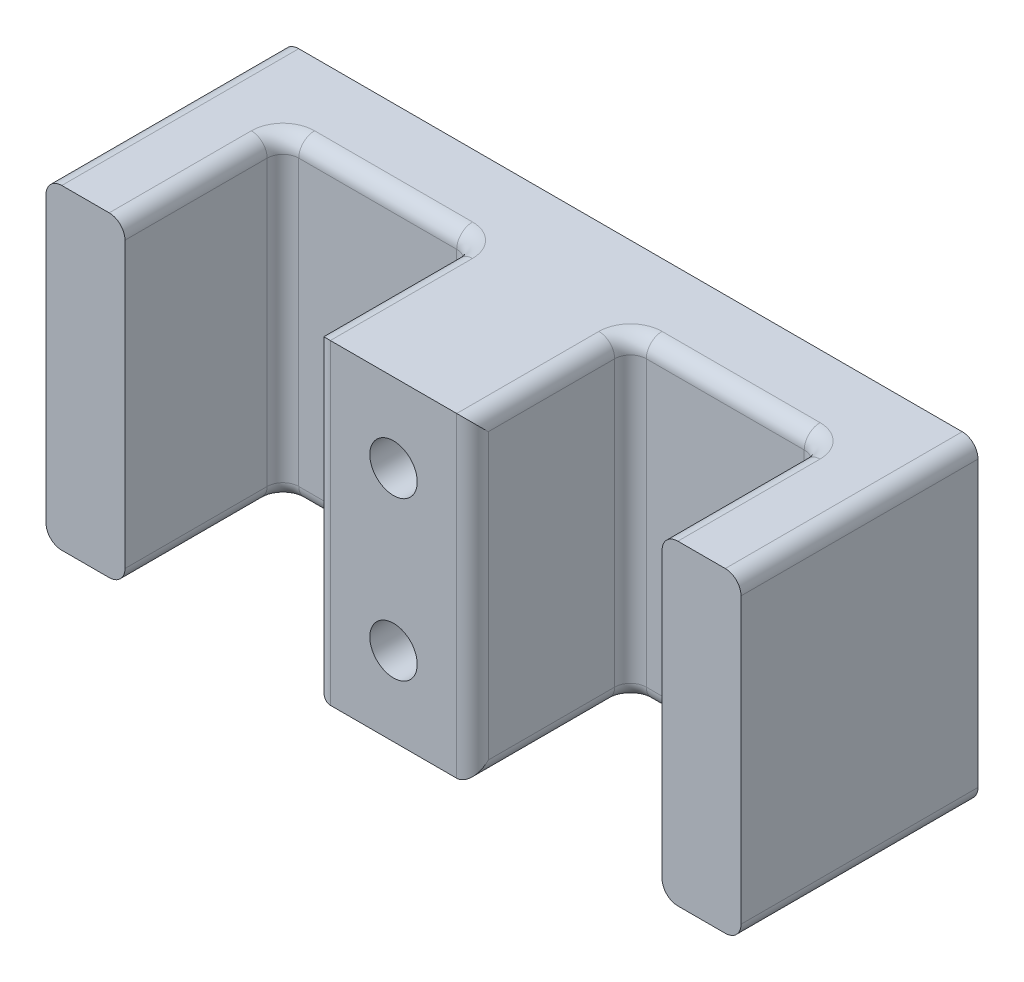
SolidWorks part; units mm, degrees
ref_plane "Front Plane" through (0, 0, 0) normal (0, 0, 1) x (1, 0, 0)
ref_plane "Top Plane" through (0, 0, 0) normal (0, 1, 0) x (1, 0, 0)
ref_plane "Right Plane" through (0, 0, 0) normal (1, 0, 0) x (0, 0, -1)
sketch "Sketch1" plane through (0, 0, 0) normal (0, 0, 1) x (1, 0, 0)
  line L0 (0, 0) -> (44, 0)
  line L1 (44, 0) -> (44, 20)
  line L2 (44, 20) -> (0, 20)
  line L3 (0, 20) -> (0, 0)
  dimension "D1" = 44
  dimension "D2" = 20
extrude "Boss-Extrude1" add sketch "Sketch1" along normal blind 5
sketch "Sketch2" plane through (0, 0, 5) normal (0, 0, 1) x (1, 0, 0)
  line L0 (0, 0) -> (5, 0)
  line L1 (0, 0) -> (44, 0) construction
  line L2 (5, 0) -> (5, 20)
  line L3 (44, 20) -> (0, 20) construction
  line L4 (5, 20) -> (0, 20)
  line L5 (0, 20) -> (0, 0)
  line L6 (17, 20) -> (27, 20)
  line L7 (27, 20) -> (27, 0)
  line L8 (27, 0) -> (17, 0)
  line L9 (17, 0) -> (17, 20)
  line L10 (44, 0) -> (44, 20)
  line L11 (44, 20) -> (39, 20)
  line L12 (39, 20) -> (39, 0)
  line L13 (39, 0) -> (44, 0)
  dimension "D1" = 5
  dimension "D2" = 5
  dimension "D3" = 10
  dimension "D4" = 12
extrude "Boss-Extrude2" add sketch "Sketch2" along normal blind 10
sketch "Sketch4" plane through (0, 0, 5) normal (0, 0, 1) x (1, 0, 0)
  line L0 (17, 20) -> (5, 20) construction
  line L1 (39, 20) -> (27, 20) construction
  line L2 (5, 0) -> (5, 20) construction
  line L3 (27, 0) -> (27, 20) construction
  circle A0 centre (11, 10) radius 1.75
  circle A1 centre (33, 10) radius 1.75
  dimension "D1" = 3.5
  dimension "D2" = 3.5
  dimension "D3" = 10
  dimension "D4" = 10
  dimension "D5" = 6
  dimension "D6" = 6
extrude "Cut-Extrude1" cut sketch "Sketch4" against normal up to next
sketch "Sketch5" plane through (0, 0, 15) normal (0, 0, 1) x (1, 0, 0)
  line L0 (17, 20) -> (17, 0) construction
  line L1 (27, 20) -> (17, 20) construction
  line L2 (17, 0) -> (27, 0) construction
  circle A0 centre (22, 15) radius 1.5
  circle A1 centre (22, 5) radius 1.5
  point P4 (0, 0)
  dimension "D1" = 3
  dimension "D2" = 3
  dimension "D3" = 5
  dimension "D4" = 5
  dimension "D5" = 5
extrude "Cut-Extrude2" cut sketch "Sketch5" against normal blind 7
fillet "Fillet1" radius 1 22 edges at (17, 20, 10) (5, 20, 10) (39, 20, 10) (27, 20, 10) (39, 0, 10) (11, 20, 5) (33, 20, 5) (39, 10, 5) (27, 10, 5) (5, 10, 5) (17, 10, 5) (27, 0, 10) (33, 0, 5) (0, 20, 7.5) (0, 0, 7.5) (5, 0, 10) (11, 0, 5) (17, 0, 10) (27, 10, 15) (17, 10, 15) (44, 20, 7.5) (44, 0, 7.5)
